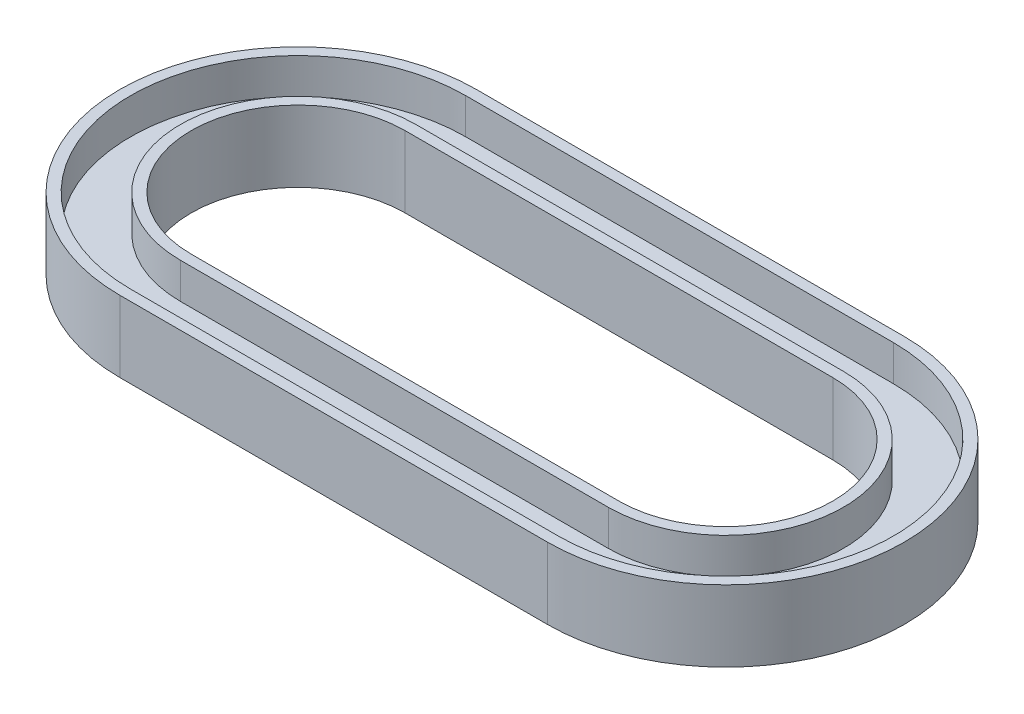
SolidWorks part; units mm, degrees
ref_plane "前基準面" through (0, 0, 0) normal (0, 0, 1) x (1, 0, 0)
ref_plane "上基準面" through (0, 0, 0) normal (0, 1, 0) x (1, 0, 0)
ref_plane "右基準面" through (0, 0, 0) normal (1, 0, 0) x (0, 0, -1)
sketch "草圖1" plane through (0, 0, 0) normal (0, 1, 0) x (1, 0, 0)
  line L0 (-60, 50) -> (60, 50)
  line L1 (-60, -50) -> (60, -50)
  line L2 (-60, -30) -> (60, -30)
  line L3 (-60, 30) -> (60, 30)
  arc A0 (60, 50) -> (60, -50) centre (60, 0) cw
  arc A1 (-60, 50) -> (-60, -50) centre (-60, 0) ccw
  arc A2 (-60, 30) -> (-60, -30) centre (-60, 0) ccw
  arc A3 (60, 30) -> (60, -30) centre (60, 0) cw
  point P6 (0, 50)
  point P8 (45.1303, 0)
  dimension "D1" = 50
  dimension "D2" = 120
  dimension "D3" = 20
extrude "填料-伸長3" add sketch "草圖1" along normal blind 10
sketch "草圖4" plane through (0, 0, 0) normal (0, 1, 0) x (1, 0, 0)
  line L0 (-60, -50) -> (60, -50) construction
  line L1 (-60, -30) -> (60, -30) construction
  line L2 (-60, 30) -> (60, 30) construction
  line L3 (-60, 50) -> (60, 50) construction
  line L4 (-60, -50) -> (60, -50)
  line L5 (-60, -30) -> (60, -30)
  line L6 (-60, 30) -> (60, 30)
  line L7 (-60, 50) -> (60, 50)
  line L8 (-60, 33) -> (60, 33)
  line L9 (-60, -33) -> (60, -33)
  line L10 (-60, -47) -> (60, -47)
  line L11 (-60, 47) -> (60, 47)
  arc A0 (60, -50) -> (60, 50) centre (60, 0) ccw construction
  arc A1 (60, -30) -> (60, 30) centre (60, 0) ccw construction
  arc A2 (-60, 30) -> (-60, -30) centre (-60, 0) ccw construction
  arc A3 (-60, 50) -> (-60, -50) centre (-60, 0) ccw construction
  arc A4 (60, -50) -> (60, 50) centre (60, 0) ccw
  arc A5 (60, -30) -> (60, 30) centre (60, 0) ccw
  arc A6 (-60, 30) -> (-60, -30) centre (-60, 0) ccw
  arc A7 (-60, 50) -> (-60, -50) centre (-60, 0) ccw
  arc A8 (60, -33) -> (60, 33) centre (60, 0) ccw
  arc A9 (-60, 33) -> (-60, -33) centre (-60, 0) ccw
  arc A10 (-60, 47) -> (-60, -47) centre (-60, 0) ccw
  arc A11 (60, -47) -> (60, 47) centre (60, 0) ccw
  dimension "D1" = 3
  dimension "D2" = 3
extrude "填料-伸長4" add sketch "草圖4" along normal blind 20 contours L8 A9 L9 A8 A6 L6 A5 L5 | L7 A7 L4 A4 A11 L10 A10 L11
